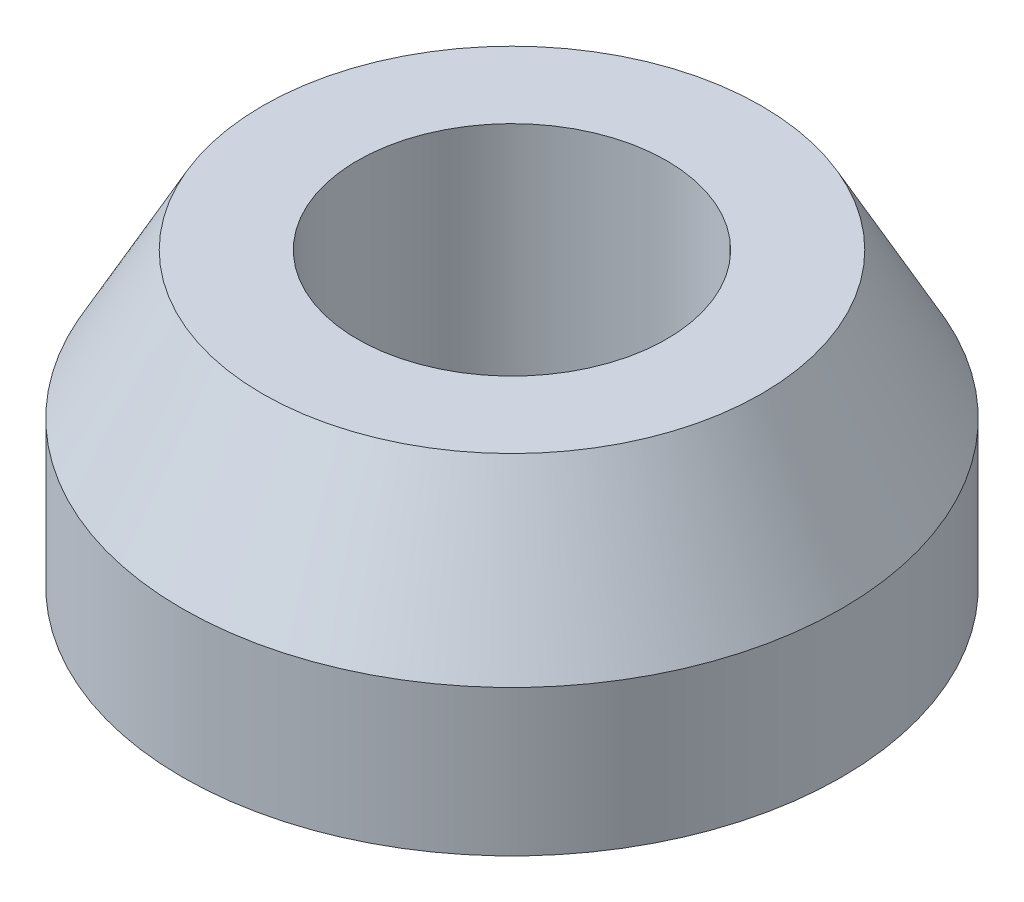
SolidWorks part; units mm, degrees
material "POLYURETHANE (11671)"
ref_plane "Front Plane" through (0, 0, 0) normal (0, 0, 1) x (1, 0, 0)
ref_plane "Top Plane" through (0, 0, 0) normal (0, 1, 0) x (1, 0, 0)
ref_plane "Right Plane" through (0, 0, 0) normal (1, 0, 0) x (0, 0, -1)
sketch "Sketch1" plane through (0, 0, 0) normal (0, 0, 1) x (1, 0, 0)
  line L0 (6.731, 0) -> (14.351, 0)
  line L1 (6.731, 0) -> (6.731, 12.7)
  line L2 (6.731, 12.7) -> (10.8585, 12.7)
  line L3 (0, 0) -> (0, 7.8878) construction
  line L4 (14.351, 0) -> (14.351, 6.35)
  line L5 (10.8585, 12.7) -> (14.351, 6.35)
  line L6 (0, 0) -> (14.351, 0) construction
  dimension "D1" = 14.351
  dimension "D2" = 4.1275
  dimension "D3" = 12.7
  dimension "D4" = 7.62
  dimension "D5" = 6.35
revolve "Revolve1" add sketch "Sketch1" angle 360 about L3
